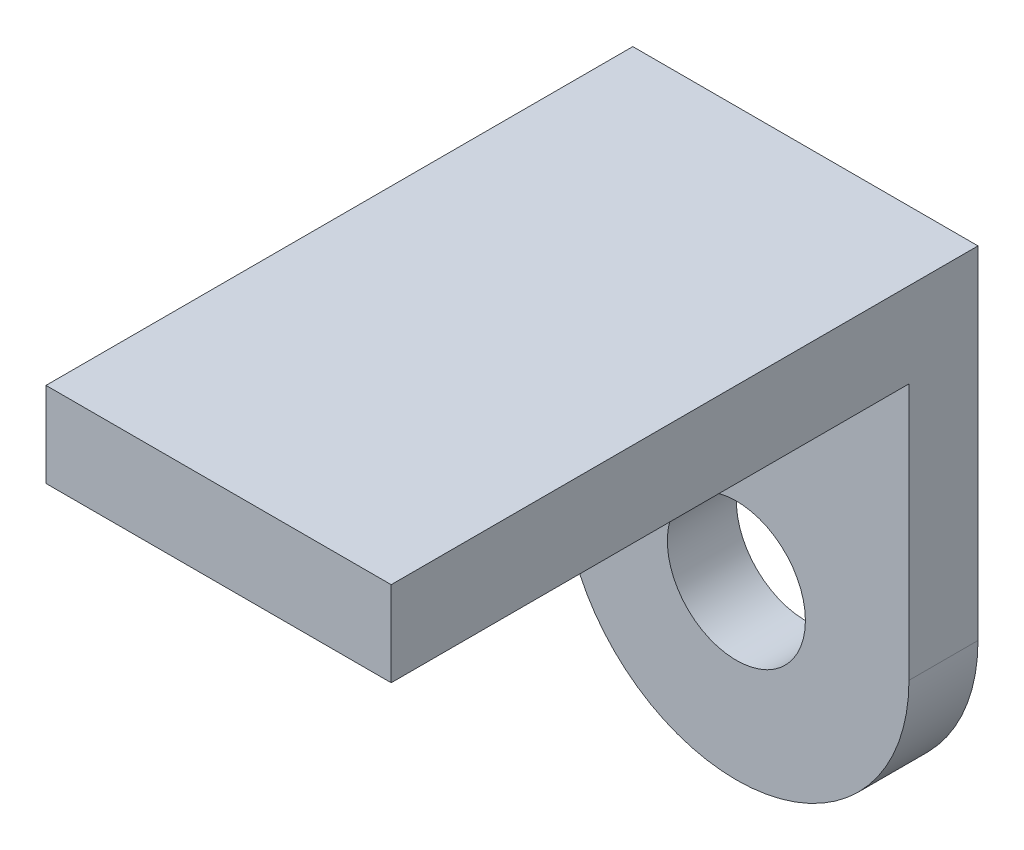
SolidWorks part; units mm, degrees
ref_plane "Piano frontale" through (0, 0, 0) normal (0, 0, 1) x (1, 0, 0)
ref_plane "Piano superiore" through (0, 0, 0) normal (0, 1, 0) x (1, 0, 0)
ref_plane "Piano destro" through (0, 0, 0) normal (1, 0, 0) x (0, 0, -1)
sketch "Schizzo1" plane through (0, 0, 0) normal (0, 0, 1) x (1, 0, 0)
  line L0 (0, 0) -> (0, 9.9) construction
  line L1 (-5, 0) -> (-5, 9.9)
  line L2 (-5, 9.9) -> (5, 9.9)
  line L3 (5, 9.9) -> (5, 0)
  circle A0 centre (0, 0) radius 2
  arc A1 (5, 0) -> (-5, 0) centre (0, 0) cw
extrude "Estrusione-Estrusione1" add sketch "Schizzo1" along normal blind 2
sketch "Schizzo2" plane through (0, 0, 2) normal (0, 0, 1) x (1, 0, 0)
  line L0 (5, 0) -> (5, 9.9) construction
  line L1 (-5, 9.9) -> (5, 9.9)
  line L2 (-5, 9.9) -> (-5, 7.4384)
  line L3 (-5, 7.4384) -> (5, 7.4384)
  line L4 (5, 9.9) -> (5, 7.4384)
extrude "Estrusione-Estrusione2" add sketch "Schizzo2" along normal blind 15 contours L2 L1 L4 L3
sketch "Schizzo4" plane through (0, 7.4384, 0) normal (0, -1, 0) x (1, 0, 0)
  line L0 (0, 17) -> (0, 2) construction
  line L1 (-5, 17) -> (5, 17) construction
  line L2 (5, 2) -> (-5, 2) construction
  text T0 "PT-003"
extrude "Estrusione-Estrusione3" add sketch "Schizzo4" along normal blind 0.2
